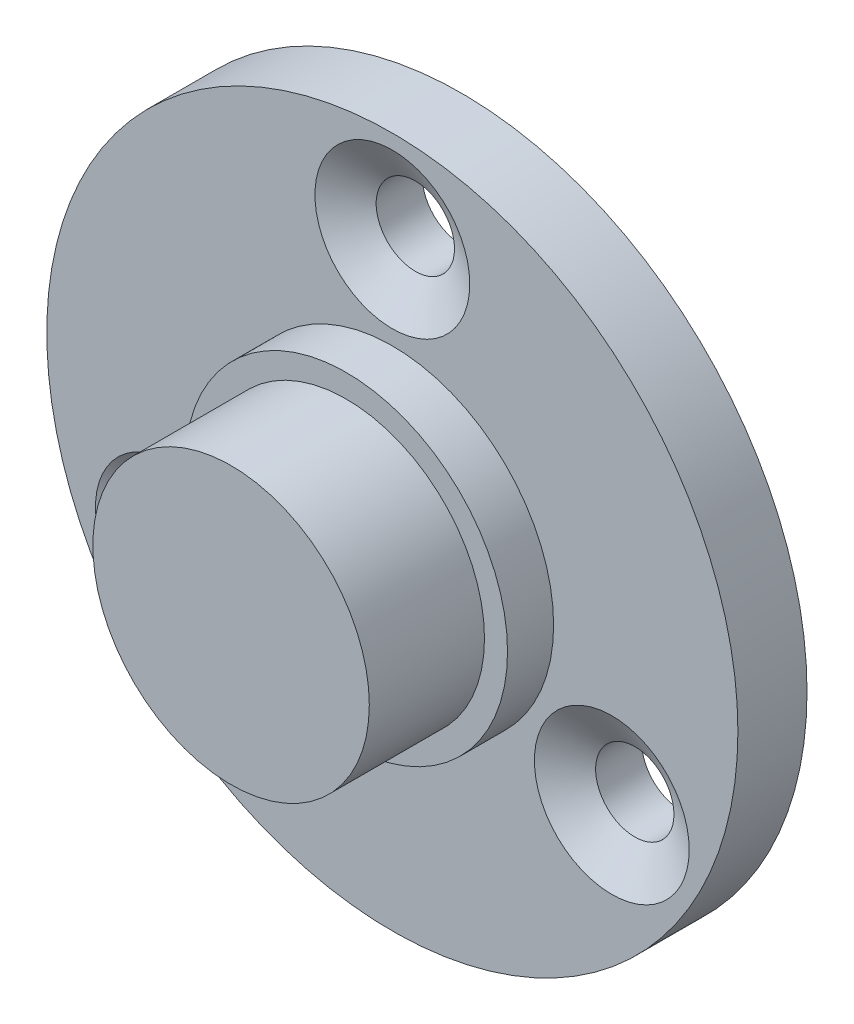
SolidWorks part; units mm, degrees
material "POM 乙缩醛共聚物"
ref_plane "前视基准面" through (0, 0, 0) normal (0, 0, 1) x (1, 0, 0)
ref_plane "上视基准面" through (0, 0, 0) normal (0, 1, 0) x (1, 0, 0)
ref_plane "右视基准面" through (0, 0, 0) normal (1, 0, 0) x (0, 0, -1)
sketch "草图1" plane through (0, 0, 0) normal (0, 0, 1) x (1, 0, 0)
  circle A0 centre (0, 0) radius 15
  dimension "D1" = 30
extrude "凸台-拉伸1" add sketch "草图1" along normal blind 3
sketch "草图2" plane through (0, 0, 3) normal (0, 0, 1) x (1, 0, 0)
  circle A0 centre (0, 0) radius 6
  dimension "D1" = 12
extrude "凸台-拉伸2" add sketch "草图2" along normal blind 7
sketch "草图3" plane through (0, 0, 3) normal (0, 0, 1) x (1, 0, 0)
  circle A0 centre (0, 0) radius 11 construction
  circle A1 centre (0, 11) radius 1.5
  circle A2 centre (9.5263, -5.5) radius 1.5
  circle A3 centre (-9.5263, -5.5) radius 1.5
  point P11 (0, 0)
  dimension "D1" = 22
  dimension "D2" = 3
  dimension "D3" = 3
hole_wizard "M3 六角凹锥坑螺钉的锥形沉头孔1" positions "3D草图3" profile "草图5" countersink size "M3" standard "ISO"
sketch3d "3D草图3"
  point P0 (0, 11, 3)
  point P3 (-9.5263, -5.5, 3)
  point P6 (9.5263, -5.5, 3)
  point P9 (0, 0, 0)
sketch "草图5" plane through (0, 11, 3) normal (1, 0, 0) x (0, -1, 0)
  line L0 (0, 0) -> (0, 15.5615)
  line L1 (0, 15.5615) -> (1.7, 14.54)
  line L2 (1.7, 14.54) -> (1.7, 0.9974)
  line L3 (1.7, 0.9974) -> (3.36, 0)
  line L5 (3.36, 0) -> (0, 0)
  line L6 (-1.7, 0.9974) -> (-3.36, 0) construction
  line L10 (0, 15.5615) -> (-1.7, 14.54) construction
  line L11 (0, -6.35) -> (0, 107.95) construction
  dimension "孔直径" = 3.4
  dimension "孔深度" = 14.54
  dimension "近端锥形沉头孔直径" = 6.72
  dimension "近端锥形沉头孔角度" = 118
  dimension "导头角度" = 118
sketch "草图6" plane through (0, 0, 3) normal (0, 0, 1) x (1, 0, 0)
  circle A0 centre (0, 0) radius 6
  circle A1 centre (0, 0) radius 7
  dimension "D1" = 14
  dimension "D2" = 12
extrude "凸台-拉伸3" add sketch "草图6" along normal blind 2
